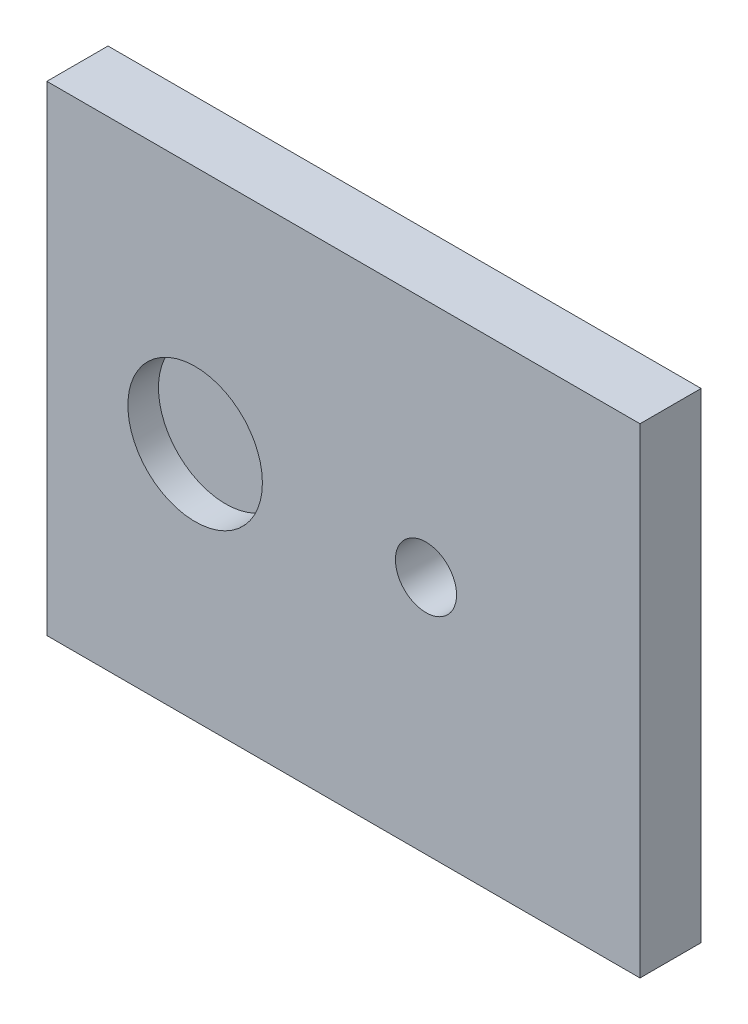
SolidWorks part; units mm, degrees
ref_plane "Front Plane" through (0, 0, 0) normal (0, 0, 1) x (1, 0, 0)
ref_plane "Top Plane" through (0, 0, 0) normal (0, 1, 0) x (1, 0, 0)
ref_plane "Right Plane" through (0, 0, 0) normal (1, 0, 0) x (0, 0, -1)
sketch "Sketch1" plane through (0, 0, 0) normal (0, 0, 1) x (1, 0, 0)
  line L1 (-48.5, -39.25) -> (48.5, -39.25)
  line L2 (-48.5, -39.25) -> (-48.5, 39.25)
  line L3 (-48.5, 39.25) -> (48.5, 39.25)
  line L4 (48.5, -39.25) -> (48.5, 39.25)
  line L5 (-48.5, -39.25) -> (48.5, 39.25) construction
  line L6 (-48.5, 39.25) -> (48.5, -39.25) construction
  point P0 (0, 0)
  dimension "D1" = 97
  dimension "D2" = 78.5
extrude "Boss-Extrude1" add sketch "Sketch1" along normal blind 10
sketch "Sketch2" plane through (0, 0, 10) normal (0, 0, 1) x (1, 0, 0)
  line L2 (48.5, -39.25) -> (48.5, 39.25) construction
  line L3 (-24.7721, 0) -> (48.5, 0) construction
  circle A1 centre (13.5, 0) radius 5
  dimension "D1" = 10
  dimension "D2" = 35
extrude "Cut-Extrude1" cut sketch "Sketch2" against normal up to next
sketch "Sketch3" plane through (0, 0, 10) normal (0, 0, 1) x (1, 0, 0)
  line L0 (-48.5, 0) -> (0, 0) construction
  line L1 (-48.5, 39.25) -> (-48.5, -39.25) construction
  circle A0 centre (-24.25, 0) radius 11
  dimension "D1" = 22
extrude "Cut-Extrude2" cut sketch "Sketch3" against normal blind 5
